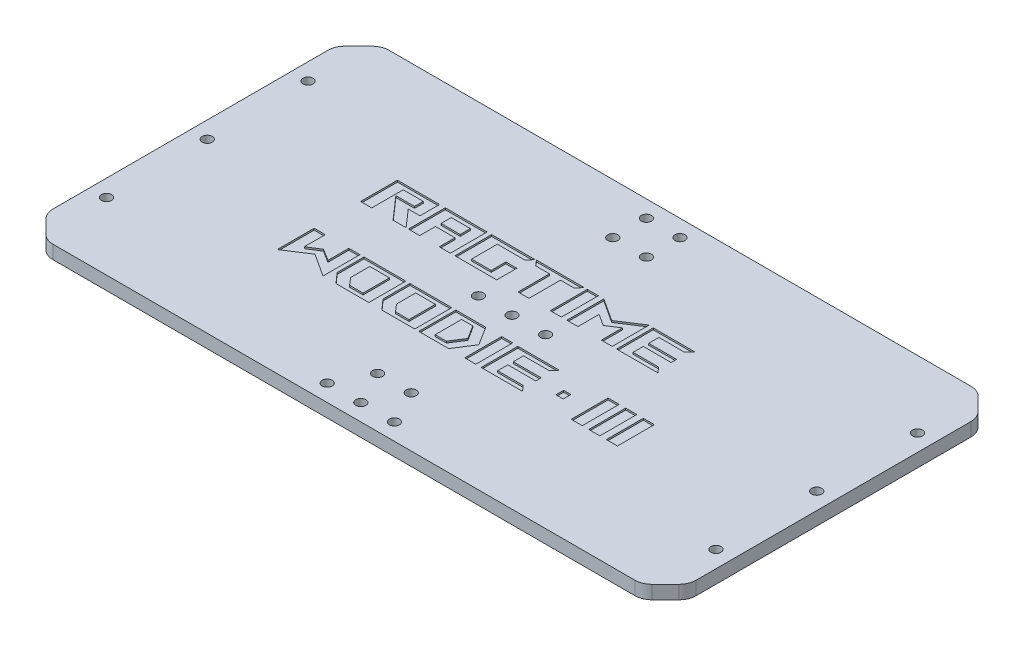
SolidWorks part; units mm, degrees
ref_plane "前视基准面" through (0, 0, 0) normal (0, 0, 1) x (1, 0, 0)
ref_plane "上视基准面" through (0, 0, 0) normal (0, 1, 0) x (1, 0, 0)
ref_plane "右视基准面" through (0, 0, 0) normal (1, 0, 0) x (0, 0, -1)
sketch "草图2" plane through (0, 0, 0) normal (0, 1, 0) x (1, 0, 0)
  line L0 (-94.2355, 44.4645) -> (-90.1645, 48.5355)
  line L1 (-86.6289, 50) -> (86.6289, 50)
  line L2 (-95.7, 40.9289) -> (-95.7, -40.9289)
  line L3 (-86.6289, -50) -> (86.6289, -50)
  line L4 (95.7, 40.9289) -> (95.7, -40.9289)
  line L5 (-95.7, 50) -> (95.7, -50) construction
  line L6 (-95.7, -50) -> (95.7, 50) construction
  line L7 (90.1645, 48.5355) -> (94.2355, 44.4645)
  line L8 (90.1645, -48.5355) -> (94.2355, -44.4645)
  line L9 (-94.2355, -44.4645) -> (-90.1645, -48.5355)
  arc A0 (90.1645, -48.5355) -> (86.6289, -50) centre (86.6289, -45) cw
  arc A1 (94.2355, -44.4645) -> (95.7, -40.9289) centre (90.7, -40.9289) ccw
  arc A2 (94.2355, 44.4645) -> (95.7, 40.9289) centre (90.7, 40.9289) cw
  arc A3 (90.1645, 48.5355) -> (86.6289, 50) centre (86.6289, 45) ccw
  arc A4 (-90.1645, -48.5355) -> (-86.6289, -50) centre (-86.6289, -45) ccw
  arc A5 (-94.2355, -44.4645) -> (-95.7, -40.9289) centre (-90.7, -40.9289) cw
  arc A6 (-94.2355, 44.4645) -> (-95.7, 40.9289) centre (-90.7, 40.9289) ccw
  arc A7 (-90.1645, 48.5355) -> (-86.6289, 50) centre (-86.6289, 45) cw
  point P0 (0, 0)
  point P16 (88.7, -50)
  point P19 (95.7, -43)
  point P22 (95.7, 43)
  point P25 (88.7, 50)
  point P28 (-88.7, -50)
  point P31 (-95.7, -43)
  point P34 (-95.7, 43)
  point P37 (-88.7, 50)
  dimension "D3" = 5
  dimension "D1" = 191.4
  dimension "D2" = 100
extrude "凸台-拉伸1" add sketch "草图2" along normal blind 4
sketch "草图3" plane through (0, 0, 0) normal (0, -1, 0) x (1, 0, 0)
  line L0 (-86.6289, 50) -> (86.6289, 50) construction
  line L1 (5, -50) -> (-5, -50) construction
  line L2 (5, -50) -> (5, 50) construction
  line L3 (5, 50) -> (-5, 50) construction
  line L4 (-5, -50) -> (-5, 50) construction
  line L5 (5, -50) -> (-5, 50) construction
  line L6 (5, 50) -> (-5, -50) construction
  line L7 (5, -45) -> (-5, -45) construction
  line L8 (0, 0) -> (29.6118, 0) construction
  line L9 (5, -35) -> (-5, -35) construction
  line L10 (86.6289, -50) -> (-86.6289, -50) construction
  line L11 (5, 25) -> (-5, 25) construction
  line L12 (5, 35) -> (-5, 35) construction
  line L13 (-90.7, 0) -> (-90.7, 30) construction
  line L14 (-86.6289, 50) -> (86.6289, 50) construction
  line L15 (0, 0) -> (0, 65.3156) construction
  line L16 (10, 45) -> (-10, 45) construction
  circle A0 centre (5, -45) radius 1.5
  circle A1 centre (-5, -45) radius 1.5
  circle A4 centre (-5, 35) radius 1.5
  circle A7 centre (5, 35) radius 1.5
  circle A12 centre (0, -35) radius 1.5 construction
  circle A13 centre (10, -35) radius 1.5 construction
  circle A14 centre (-10, -35) radius 1.5 construction
  circle A15 centre (0, 0) radius 1.5
  circle A16 centre (10, 0) radius 1.5
  circle A17 centre (-10, 0) radius 1.5
  circle A18 centre (0, 25) radius 1.5 construction
  circle A19 centre (10, 25) radius 1.5 construction
  circle A20 centre (-10, 25) radius 1.5 construction
  circle A21 centre (-5, -35) radius 1.5
  circle A22 centre (5, -35) radius 1.5
  circle A23 centre (5, 25) radius 1.5 construction
  circle A24 centre (-5, 25) radius 1.5 construction
  circle A25 centre (-90.7, 0) radius 1.5
  circle A26 centre (-90.7, 30) radius 1.5
  circle A27 centre (-90.7, -30) radius 1.5
  circle A28 centre (90.7, -30) radius 1.5
  circle A29 centre (90.7, 0) radius 1.5
  circle A30 centre (90.7, 30) radius 1.5
  circle A31 centre (0, 45) radius 1.5
  circle A32 centre (10, 45) radius 1.5
  circle A33 centre (-10, 45) radius 1.5
  point P0 (0, 0)
  dimension "D2" = 3
  dimension "D6" = 3
  dimension "D9" = 10
  dimension "D11" = 3
  dimension "D14" = 3
  dimension "D1" = 10
  dimension "D3" = 5
  dimension "D4" = 15
  dimension "D5" = 10
  dimension "D7" = 10
  dimension "D8" = 10
  dimension "D10" = 10
  dimension "D12" = 10
  dimension "D13" = 10
  dimension "D15" = 20
  dimension "D16" = 10
  dimension "D17" = 10
  dimension "D18" = 5
extrude "切除-拉伸1" cut sketch "草图3" against normal through all
sketch "草图4" plane through (0, 4, 0) normal (0, 1, 0) x (1, 0, 0)
  text T0 "Ragtime\r\nWoodie · III" font "ROG Fonts" height 11
extrude "切除-拉伸2" cut sketch "草图4" against normal blind 0.5
